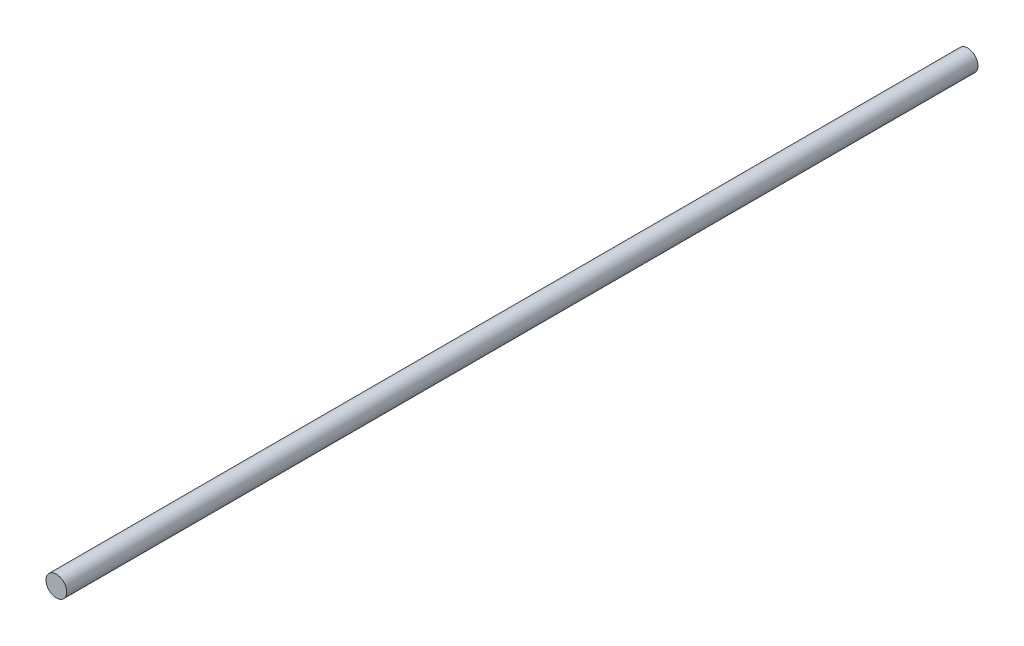
SolidWorks part; units mm, degrees
material "Chrome Stainless Steel"
ref_plane "Front Plane" through (0, 0, 0) normal (0, 0, 1) x (1, 0, 0)
ref_plane "Top Plane" through (0, 0, 0) normal (0, 1, 0) x (1, 0, 0)
ref_plane "Right Plane" through (0, 0, 0) normal (1, 0, 0) x (0, 0, -1)
sketch "Sketch1" plane through (0, 0, 0) normal (0, 0, 1) x (1, 0, 0)
  circle A0 centre (0, 0) radius 12.7
extrude "Boss-Extrude1" add sketch "Sketch1" along normal blind 1117.6
